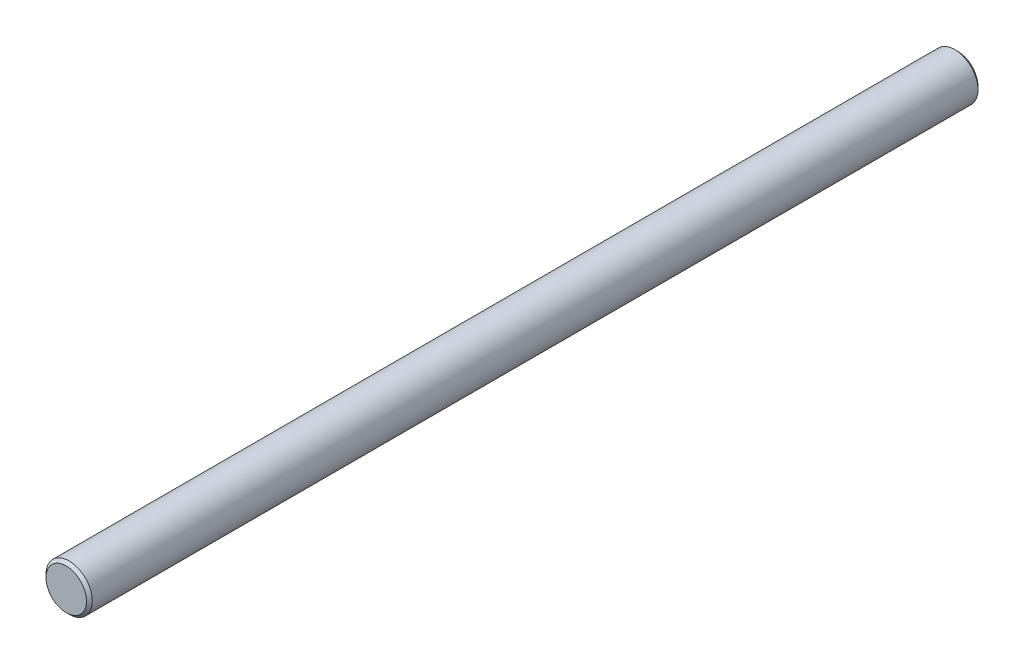
SolidWorks part; units mm, degrees
ref_plane "Front Plane" through (0, 0, 0) normal (0, 0, 1) x (1, 0, 0)
ref_plane "Top Plane" through (0, 0, 0) normal (0, 1, 0) x (1, 0, 0)
ref_plane "Right Plane" through (0, 0, 0) normal (1, 0, 0) x (0, 0, -1)
sketch "Sketch1" plane through (0, 0, 0) normal (0, 0, 1) x (1, 0, 0)
  circle A0 centre (0, 0) radius 4
  dimension "D1" = 8
extrude "Boss-Extrude1" add sketch "Sketch1" along normal mid plane 154
chamfer "Chamfer1" distance 0.5 angle 45 2 edges at (4, 0, 77) (4, 0, -77)
